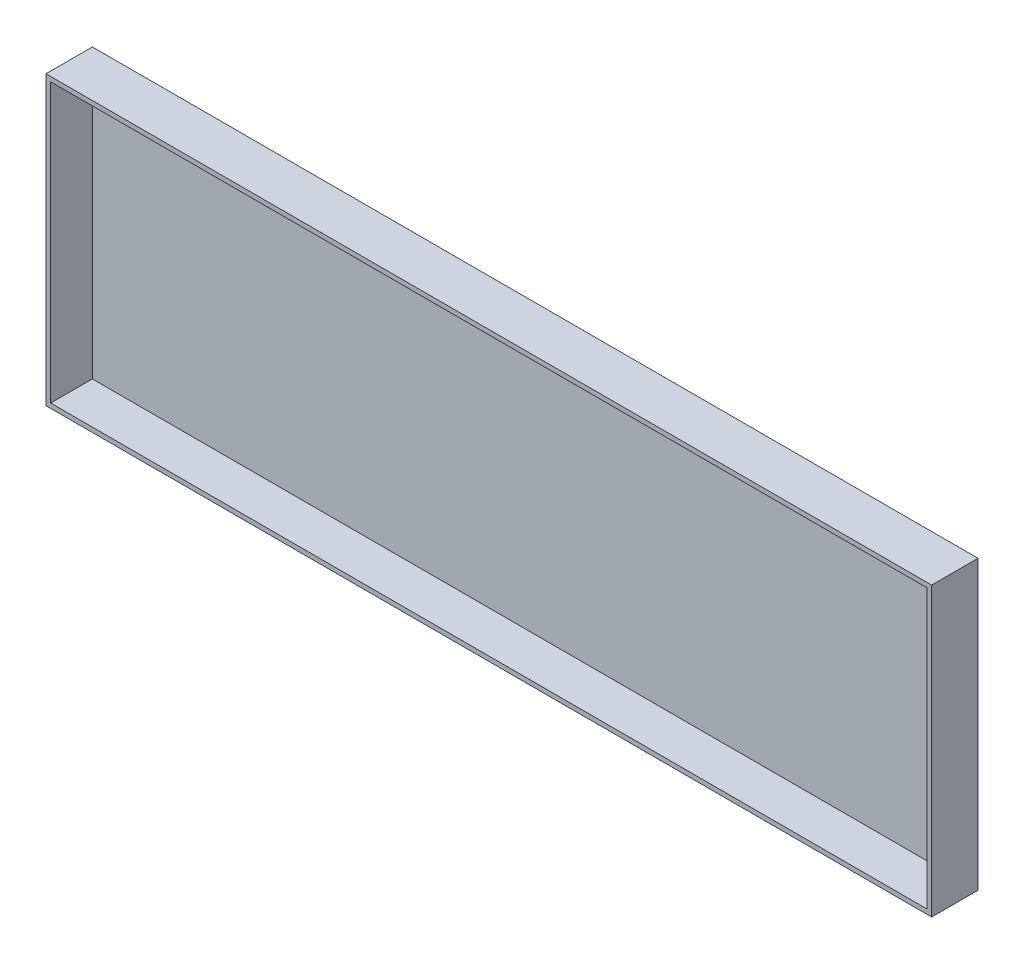
SolidWorks part; units mm, degrees
material "Acrylic (Medium-high impact)"
ref_plane "Front Plane" through (0, 0, 0) normal (0, 0, 1) x (1, 0, 0)
ref_plane "Top Plane" through (0, 0, 0) normal (0, 1, 0) x (1, 0, 0)
ref_plane "Right Plane" through (0, 0, 0) normal (1, 0, 0) x (0, 0, -1)
sketch "Sketch1" plane through (0, 0, 0) normal (0, 0, 1) x (1, 0, 0)
  line L1 (-477.5, -155) -> (477.5, -155)
  line L2 (-477.5, -155) -> (-477.5, 155)
  line L3 (-477.5, 155) -> (477.5, 155)
  line L4 (477.5, -155) -> (477.5, 155)
  line L5 (-477.5, -155) -> (477.5, 155) construction
  line L6 (-477.5, 155) -> (477.5, -155) construction
  point P0 (0, 0)
extrude "Boss-Extrude1" add sketch "Sketch1" along normal blind 5
sketch "Sketch2" plane through (0, 0, 0) normal (0, 0, 1) x (1, 0, 0)
  line L5 (-477.5, 125.5264) -> (-472.5, 125.5264) construction
  line L18 (-477.5, 155) -> (477.5, 155)
  line L19 (-477.5, 155) -> (-477.5, -155)
  line L20 (-477.5, -155) -> (477.5, -155)
  line L21 (477.5, 155) -> (477.5, -155)
  line L22 (-472.5, 155) -> (-472.5, 150) construction
  line L23 (477.5, -150) -> (472.5, -150) construction
  line L24 (472.5, -150) -> (472.5, -155) construction
  line L26 (472.5, -150) -> (-472.5, -150)
  line L27 (472.5, -150) -> (472.5, 150)
  line L28 (472.5, 150) -> (-472.5, 150)
  line L29 (-472.5, -150) -> (-472.5, 150)
extrude "Boss-Extrude2" add sketch "Sketch2" along normal blind 45 from surface at 5 starting at face at (0, 0, 5)
